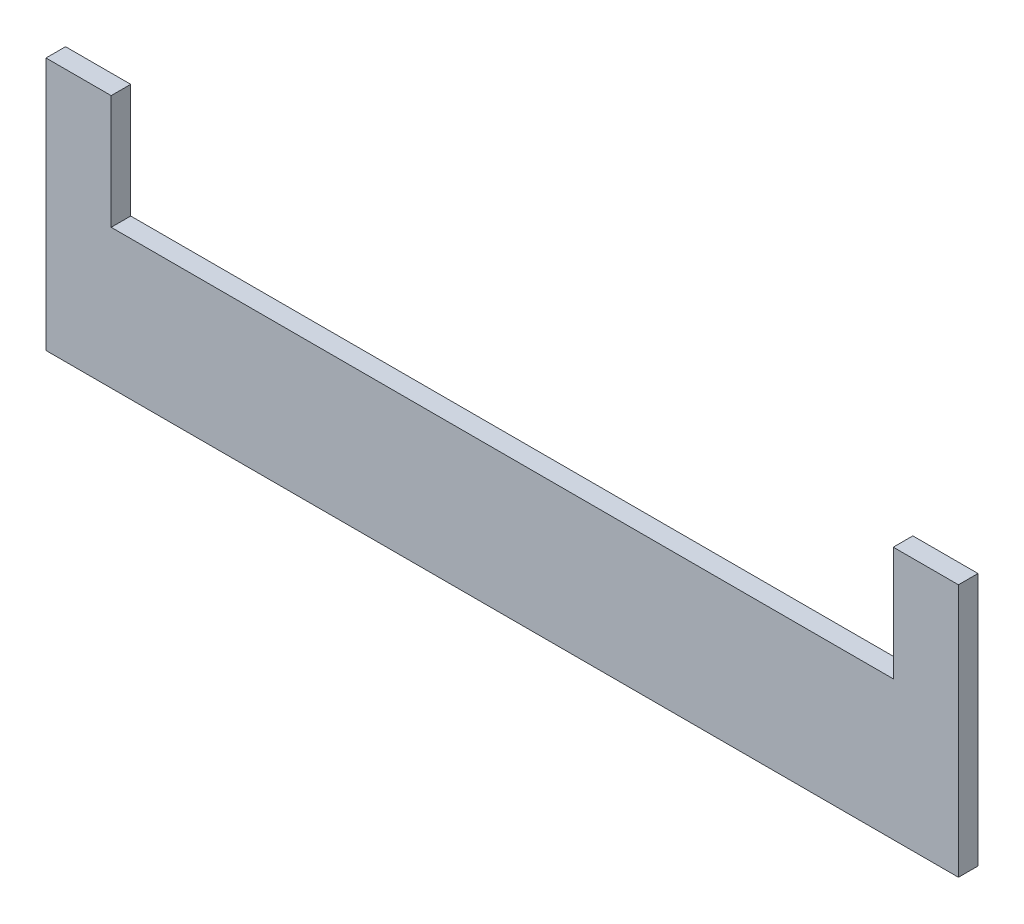
SolidWorks part; units mm, degrees
ref_plane "Front Plane" through (0, 0, 0) normal (0, 0, 1) x (1, 0, 0)
ref_plane "Top Plane" through (0, 0, 0) normal (0, 1, 0) x (1, 0, 0)
ref_plane "Right Plane" through (0, 0, 0) normal (1, 0, 0) x (0, 0, -1)
sketch "Sketch1" plane through (0, 0, 0) normal (0, 0, 1) x (1, 0, 0)
  line L0 (0, 0) -> (0, 13.0856) construction
  line L1 (28, 0) -> (-28, 0)
  line L2 (-28, 0) -> (-28, 15.549)
  line L3 (24, 8.549) -> (-24, 8.549)
  line L4 (-28, 15.549) -> (-24, 15.549)
  line L5 (-24, 15.549) -> (-24, 8.549)
  line L6 (24, 15.549) -> (24, 8.549)
  line L7 (28, 15.549) -> (24, 15.549)
  line L8 (28, 0) -> (28, 15.549)
  point P11 (0, 8.549)
  dimension "D1" = 28
  dimension "D2" = 8.549
  dimension "D3" = 4
  dimension "D4" = 7
extrude "Boss-Extrude1" add sketch "Sketch1" along normal blind 1.2
